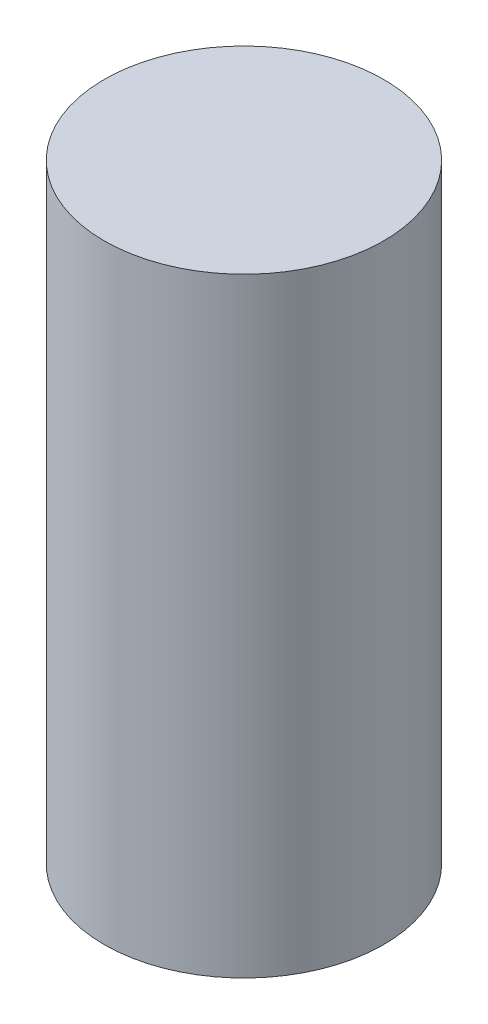
SolidWorks part; units mm, degrees
material "Natural Rubber"
ref_plane "Front Plane" through (0, 0, 0) normal (0, 0, 1) x (1, 0, 0)
ref_plane "Top Plane" through (0, 0, 0) normal (0, 1, 0) x (1, 0, 0)
ref_plane "Right Plane" through (0, 0, 0) normal (1, 0, 0) x (0, 0, -1)
sketch "Sketch1" plane through (0, 0, 0) normal (0, 1, 0) x (1, 0, 0)
  circle A0 centre (0, 0) radius 0.635
  dimension "D1" = 1.27
extrude "Boss-Extrude1" add sketch "Sketch1" along normal blind 2.7686
